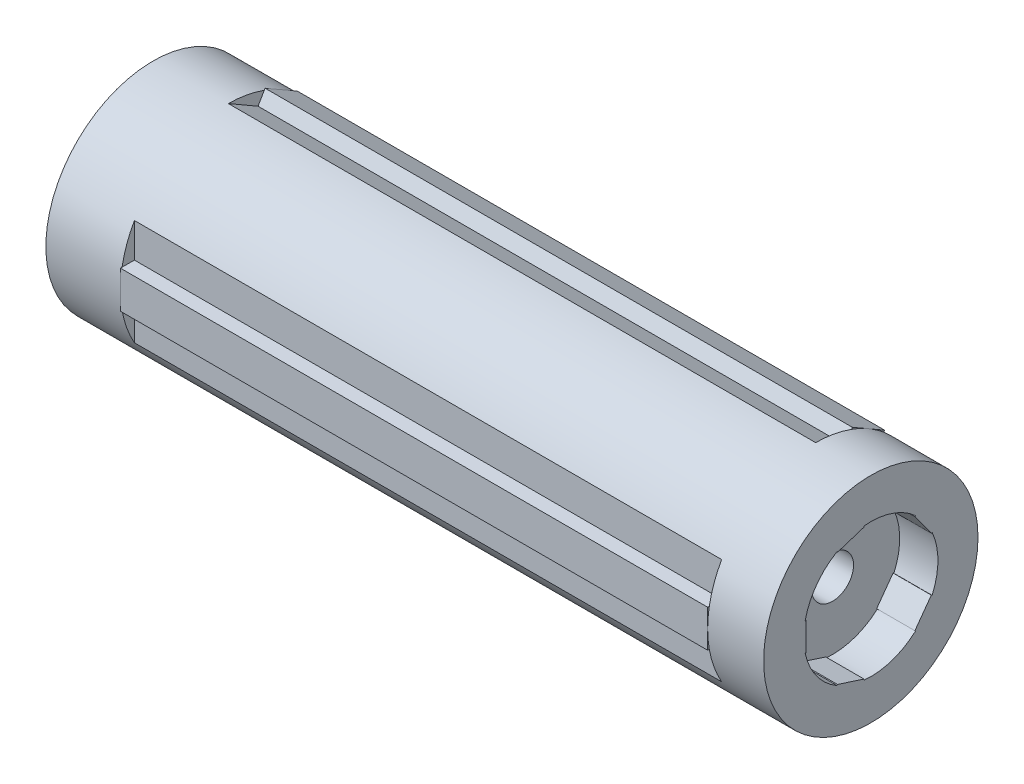
SolidWorks part; units mm, degrees
material "PVC hart"
ref_plane "Ebene vorne" through (0, 0, 0) normal (0, 0, 1) x (1, 0, 0)
ref_plane "Ebene oben" through (0, 0, 0) normal (0, 1, 0) x (1, 0, 0)
ref_plane "Ebene rechts" through (0, 0, 0) normal (1, 0, 0) x (0, 0, -1)
sketch "Skizze1" plane through (0, 0, 0) normal (1, 0, 0) x (0, 0, -1)
  circle A0 centre (0, 0) radius 11.5
  dimension "D1" = 23
extrude "Aufsatz-Linear austragen1" add sketch "Skizze1" along normal blind 77
sketch "Skizze2" plane through (77, 0, 0) normal (1, 0, 0) x (0, 0, -1)
  line L0 (-15.3822, 0) -> (15.9559, 0) construction
  line L1 (-7.0405, 1.5073) -> (-6.9405, 1.5073)
  line L2 (-6.9405, 1.5073) -> (-6.9405, -1.4927)
  line L3 (-6.9405, -1.4927) -> (-7.0436, -1.4927)
  line L4 (-0.7421, 7.1617) -> (-0.7112, 7.0666)
  line L5 (-0.7112, 7.0666) -> (-3.5643, 6.1395)
  line L6 (-3.5643, 6.1395) -> (-3.5962, 6.2376)
  line L7 (6.5818, 2.9188) -> (6.5009, 2.86)
  line L8 (6.5009, 2.86) -> (4.7376, 5.2871)
  line L9 (4.7376, 5.2871) -> (4.821, 5.3477)
  line L10 (4.8099, -5.3577) -> (4.729, -5.2989)
  line L11 (4.729, -5.2989) -> (6.4923, -2.8719)
  line L12 (6.4923, -2.8719) -> (6.5757, -2.9325)
  line L13 (-3.6092, -6.2301) -> (-3.5783, -6.135)
  line L14 (-3.5783, -6.135) -> (-0.7251, -7.062)
  line L15 (-0.7251, -7.062) -> (-0.757, -7.1601)
  arc A0 (-7.0436, -1.4927) -> (-3.6092, -6.2301) centre (0, 0) ccw
  arc A1 (-3.5962, 6.2376) -> (-7.0405, 1.5073) centre (0, 0) ccw
  arc A2 (4.821, 5.3477) -> (-0.7421, 7.1617) centre (0, 0) ccw
  arc A3 (6.5757, -2.9325) -> (6.5818, 2.9188) centre (0, 0) ccw
  arc A4 (-0.757, -7.1601) -> (4.8099, -5.3577) centre (0, 0) ccw
  point P28 (0, 0)
  dimension "D1" = 14.4
  dimension "D2" = 3
  dimension "D3" = 0.1
  dimension "D4" = 5
extrude "Schnitt-Linear austragen1" cut sketch "Skizze2" against normal blind 4.1
sketch "Skizze3" plane through (72.9, 0, 0) normal (1, 0, 0) x (0, 0, -1)
  circle A0 centre (0, 0) radius 2.25
  dimension "D1" = 4.5
extrude "Schnitt-Linear austragen2" cut sketch "Skizze3" against normal blind 3
sketch "Skizze4" plane through (0, 0, 0) normal (-1, 0, 0) x (0, 0, 1)
  circle A0 centre (0, 0) radius 9.6
  dimension "D1" = 19.2
extrude "Schnitt-Linear austragen3" cut sketch "Skizze4" against normal blind 12.75
sketch "Skizze7" plane through (77, 0, 0) normal (1, 0, 0) x (0, 0, -1)
  line L0 (0, 13.4409) -> (0, -14.2481) construction
  line L1 (-11.5, 7.5) -> (-10, 7.5)
  line L2 (-11.5, 7.5) -> (-11.5, -7.5)
  line L3 (-11.5, -7.5) -> (-10, -7.5)
  line L4 (-10, 7.5) -> (-10, -7.5)
  dimension "D1" = 1.5
  dimension "D2" = 15
  dimension "D3" = 10
extrude "Schnitt-Linear austragen4" cut sketch "Skizze7" against normal blind 63 from offset 6 offset against normal yes
sketch "Skizze8" plane through (0, 0, 10) normal (0, 0, 1) x (1, 0, 0)
  line L0 (71, -5.6789) -> (71, 5.6789) construction
  line L1 (8, 2) -> (71, 2)
  line L2 (8, 2) -> (8, -2)
  line L3 (8, -2) -> (71, -2)
  line L4 (71, 2) -> (71, -2)
  line L5 (8, 2) -> (71, -2) construction
  line L6 (8, -2) -> (71, 2) construction
  line L7 (12.65, 0) -> (-12.65, 0) construction
  point P0 (39.5, 0)
  dimension "D1" = 31.5
  dimension "D3" = 63
  dimension "D4" = 4
extrude "Aufsatz-Linear austragen2" add sketch "Skizze8" along normal blind 1.5
sketch "Skizze10" plane through (12.75, 0, 0) normal (-1, 0, 0) x (0, 0, 1)
  line L1 (4.1398, -2.2968) -> (4.059, 2.4368)
  line L2 (4.059, 2.4368) -> (-0.0809, 4.7336)
  line L3 (-0.0809, 4.7336) -> (-4.1398, 2.2968)
  line L4 (-4.1398, 2.2968) -> (-4.059, -2.4368)
  line L5 (-4.059, -2.4368) -> (0.0809, -4.7336)
  line L6 (0.0809, -4.7336) -> (4.1398, -2.2968)
  circle A0 centre (0, 0) radius 4.1 construction
  dimension "D1" = 8.2
extrude "Schnitt-Linear austragen6" cut sketch "Skizze10" against normal blind 13.5
sketch "Skizze12" plane through (26.25, 0, 0) normal (-1, 0, 0) x (0, 0, 1)
  circle A0 centre (0, 0) radius 3.1
  dimension "D1" = 6.2
extrude "Schnitt-Linear austragen7" cut sketch "Skizze12" against normal blind 2
pattern_circular "Kreismuster3" count 3 over 360 about axis through (0, 0, 0) along (1, 0, 0) of "Aufsatz-Linear austragen2", "Schnitt-Linear austragen4"
sketch "Skizze13" plane through (69.9, 0, 0) normal (1, 0, 0) x (0, 0, -1)
  circle A0 centre (0, 0) radius 8.5
extrude "Schnitt-Linear austragen8" cut sketch "Skizze13" against normal blind 40
